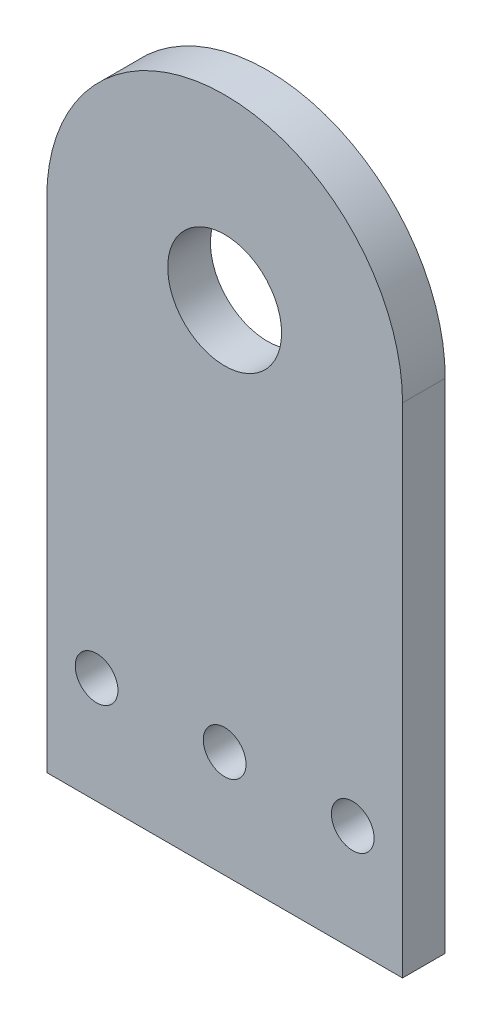
SolidWorks part; units mm, degrees
material "Thornel Mat VMA"
ref_plane "前视基准面" through (0, 0, 0) normal (0, 0, 1) x (1, 0, 0)
ref_plane "上视基准面" through (0, 0, 0) normal (0, 1, 0) x (1, 0, 0)
ref_plane "右视基准面" through (0, 0, 0) normal (1, 0, 0) x (0, 0, -1)
sketch "草图2" plane through (0, 0, 0) normal (0, 0, 1) x (1, 0, 0)
  line L1 (-12.5, 17.5) -> (12.5, 17.5) construction
  line L2 (-12.5, 17.5) -> (-12.5, -17.5)
  line L3 (-12.5, -17.5) -> (12.5, -17.5)
  line L4 (12.5, 17.5) -> (12.5, -17.5)
  line L5 (-12.5, 17.5) -> (12.5, -17.5) construction
  line L6 (-12.5, -17.5) -> (12.5, 17.5) construction
  arc A0 (12.5, 17.5) -> (-12.5, 17.5) centre (0, 17.5) ccw
  point P0 (0, 0)
  dimension "D1" = 25
  dimension "D2" = 35
extrude "凸台-拉伸1" add sketch "草图2" along normal blind 3
sketch "草图3" plane through (0, 0, 3) normal (0, 0, 1) x (1, 0, 0)
  line L0 (0, -17.5) -> (0, 17.5) construction
  line L1 (-12.5, -17.5) -> (12.5, -17.5) construction
  circle A0 centre (0, 17.5) radius 4
  dimension "D1" = 8
  dimension "D2" = 35
extrude "切除-拉伸1" cut sketch "草图3" against normal through all
sketch "草图4" plane through (0, 0, 3) normal (0, 0, 1) x (1, 0, 0)
  line L0 (-12.5, -10) -> (12.5, -10) construction
  line L1 (-12.5, 17.5) -> (-12.5, -17.5) construction
  line L2 (12.5, -17.5) -> (12.5, 17.5) construction
  line L3 (0, -10) -> (0, -17.5) construction
  line L4 (-12.5, -17.5) -> (12.5, -17.5) construction
  circle A0 centre (-9, -10) radius 1.5
  circle A1 centre (0, -10) radius 1.5
  circle A2 centre (9, -10) radius 1.5
  dimension "D1" = 3
  dimension "D2" = 7.5
  dimension "D3" = 9
extrude "切除-拉伸2" cut sketch "草图4" against normal through all
